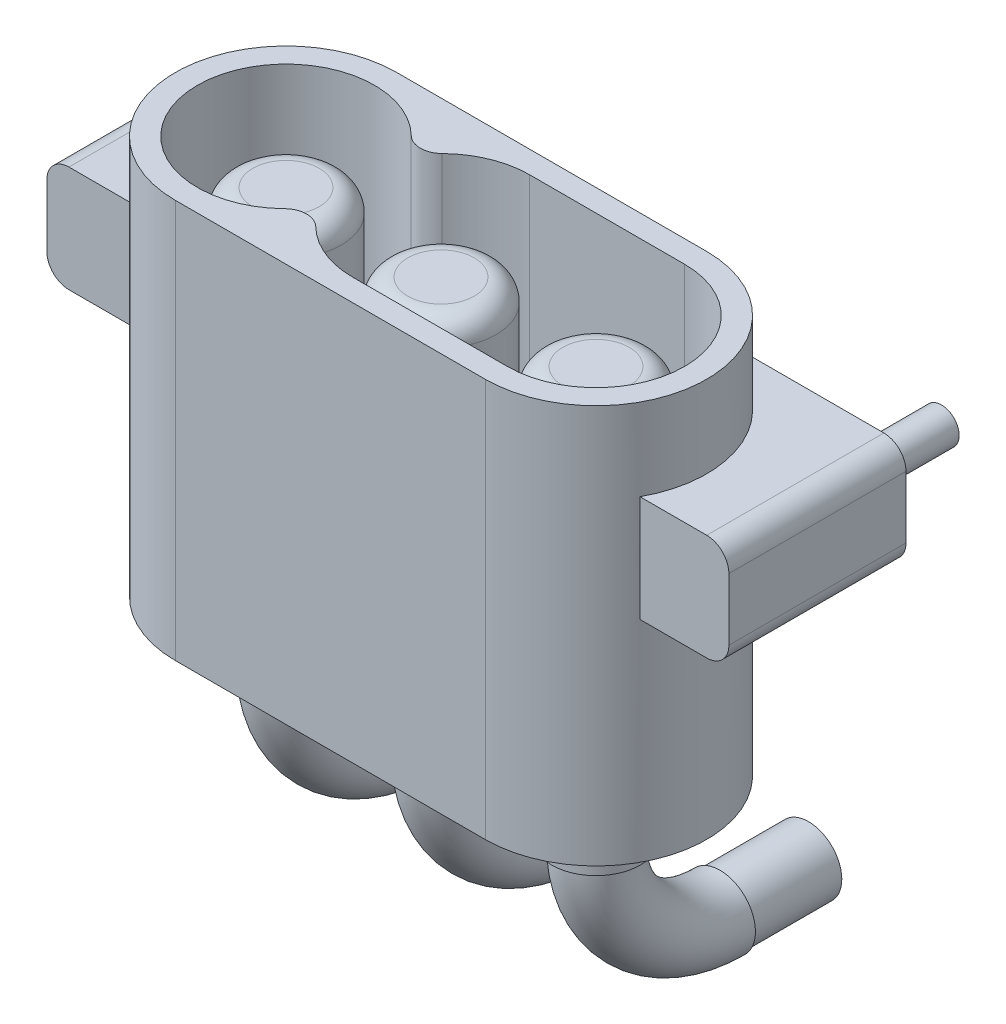
SolidWorks part; units mm, degrees
material "5052-H38"
ref_plane "Front" through (0, 0, 0) normal (0, 0, 1) x (1, 0, 0)
ref_plane "Top" through (0, 0, 0) normal (0, 1, 0) x (1, 0, 0)
ref_plane "Right" through (0, 0, 0) normal (1, 0, 0) x (0, 0, -1)
sketch "ｽｹｯﾁ1" plane through (0, 0, 0) normal (0, 0, 1) x (1, 0, 0)
  circle A0 centre (0, 0) radius 0.75
  dimension "D1" = 1.5
extrude "ﾎﾞｽ - 押し出し1" add sketch "ｽｹｯﾁ1" against normal blind 2
sketch "ｽｹｯﾁ2" plane through (0, 0, 0) normal (0, 0, 1) x (1, 0, 0)
  circle A0 centre (0, 0) radius 0.8
  dimension "D1" = 1.6
sketch "ｽｹｯﾁ3" plane through (0, 0, 0) normal (1, 0, 0) x (0, 0, -1)
  line L0 (0, 0) -> (0, 2.8) construction
  line L1 (0, 2.8) -> (-2.8, 2.8) construction
  arc A0 (0, 0) -> (-2.8, 2.8) centre (0, 2.8) cw
  dimension "D1" = 2.8
sweep "ｽｲｰﾌﾟ1" add profiles "ｽｹｯﾁ2" path "ｽｹｯﾁ3"
sketch "ｽｹｯﾁ4" plane through (0, 2.8, 0) normal (0, 1, 0) x (1, 0, 0)
  circle A0 centre (0, -2.8) radius 1
  circle A1 centre (0, -2.8) radius 0.8 construction
  point P2 (0, -2.8)
  dimension "D1" = 2
extrude "ﾎﾞｽ - 押し出し2" add sketch "ｽｹｯﾁ4" along normal blind 1.25
sketch "ｽｹｯﾁ5" plane through (0, 4.05, 0) normal (0, 1, 0) x (1, 0, 0)
  line L0 (0, -5.3) -> (7, -5.3)
  line L1 (0, -0.3) -> (7, -0.3)
  arc A0 (0, -0.3) -> (0, -5.3) centre (0, -2.8) ccw
  arc A1 (7, -0.3) -> (7, -5.3) centre (7, -2.8) cw
  point P7 (-5.2676, -1.0483)
  point P8 (0, 0)
  point P9 (-6.9069, -1.5256)
  point P10 (7.2048, -4.812)
  dimension "D2" = 2.5
  dimension "D1" = 7
extrude "ﾎﾞｽ - 押し出し3" add sketch "ｽｹｯﾁ5" along normal blind 9
sketch "ｽｹｯﾁ6" plane through (0, 0, 0) normal (0, 0, 1) x (1, 0, 0)
  line L1 (0, 10) -> (-3, 10) construction
  line L7 (0, 0) -> (0, 10) construction
  line L8 (0, 13.05) -> (0, 4.05) construction
  line L9 (0, 10) -> (10, 10) construction
  circle A0 centre (10, 10) radius 0.4
  circle A1 centre (-3, 10) radius 0.4
  dimension "D3" = 0.8
  dimension "D1" = 10
  dimension "D2" = 10
  dimension "D4" = 3
extrude "ﾎﾞｽ - 押し出し4" add sketch "ｽｹｯﾁ6" against normal blind 2 separate body
sketch "ｽｹｯﾁ7" plane through (0, 0, 0) normal (0, 0, 1) x (1, 0, 0)
  line L1 (7, 8.8) -> (11.2, 8.8)
  line L2 (7, 8.8) -> (7, 11.2)
  line L3 (7, 11.2) -> (11.2, 11.2)
  line L4 (11.2, 8.8) -> (11.2, 11.2)
  line L5 (11.2, 10) -> (10, 10) construction
  line L7 (-4.2, 11.2) -> (-4.2, 8.8)
  line L8 (-4.2, 8.8) -> (0, 8.8)
  line L9 (0, 8.8) -> (0, 11.2)
  line L10 (0, 11.2) -> (-4.2, 11.2)
  line L12 (0, 13.05) -> (0, 4.05) construction
  line L13 (7, 13.05) -> (7, 4.05) construction
  point P0 (10, 10)
  dimension "D1" = 4.2
  dimension "D2" = 2.4
extrude "ﾎﾞｽ - 押し出し5" add sketch "ｽｹｯﾁ7" along normal blind 4
sketch "ｽｹｯﾁ8" plane through (0, 13.05, 0) normal (0, 1, 0) x (1, 0, 0)
  line L0 (7, -0.8) -> (0, -0.8)
  line L1 (0, -4.8) -> (7, -4.8)
  arc A2 (0, -4.8) -> (0, -0.8) centre (0, -2.8) cw
  arc A3 (7, -4.8) -> (7, -0.8) centre (7, -2.8) ccw
  point P8 (0, 0)
  point P10 (0, 0)
  dimension "D2" = 2
extrude "ｶｯﾄ - 押し出し3" cut sketch "ｽｹｯﾁ8" against normal blind 7
sketch "ｽｹｯﾁ9" plane through (0, 6.05, 0) normal (0, 1, 0) x (1, 0, 0)
  circle A0 centre (0, -2.8) radius 1.25
  arc A1 (0, -0.3) -> (0, -5.3) centre (0, -2.8) ccw construction
  dimension "D1" = 2.5
extrude "ﾎﾞｽ - 押し出し7" add sketch "ｽｹｯﾁ9" along normal blind 6
pattern_linear "直線ﾊﾟﾀｰﾝ2" count 3 spacing 3.5 along (1, 0, 0) of "ﾎﾞｽ - 押し出し1", "ｽｲｰﾌﾟ1", "ﾎﾞｽ - 押し出し2", "ﾎﾞｽ - 押し出し7"
ref_plane "平面2" through (0, 0, 2.8) normal (0, 0, -1) x (-1, 0, 0)
sketch "ｽｹｯﾁ10" plane through (0, 13.05, 0) normal (0, 1, 0) x (1, 0, 0)
  line L6 (0, -0.8) -> (3.5, -0.8)
  line L7 (7, -0.8) -> (0, -0.8) construction
  arc A5 (0, -0.8) -> (1.75, -1.8318) centre (0, -2.8) cw
  arc A6 (3.5, -0.8) -> (1.75, -1.8318) centre (3.5, -2.8) ccw
  point P11 (0, 0)
extrude "ﾎﾞｽ - 押し出し8" add sketch "ｽｹｯﾁ10" against normal up to next
mirror "ﾐﾗｰ19" about plane through (0, 0, 2.8) normal (0, 0, -1) of "ﾎﾞｽ - 押し出し8"
fillet "ﾌｨﾚｯﾄ1" radius 0.5 4 edges at (-4.2, 11.2, 2) (11.2, 8.8, 2) (11.2, 11.2, 2) (-4.2, 8.8, 2)
fillet "ﾌｨﾚｯﾄ3" radius 0.5 2 edges at (1.75, 9.55, 3.7682) (1.75, 9.55, 1.8318)
fillet "ﾌｨﾚｯﾄ4" radius 0.5 3 edges at (7, 12.05, 4.05) (3.5, 12.05, 4.05) (0, 12.05, 4.05)
